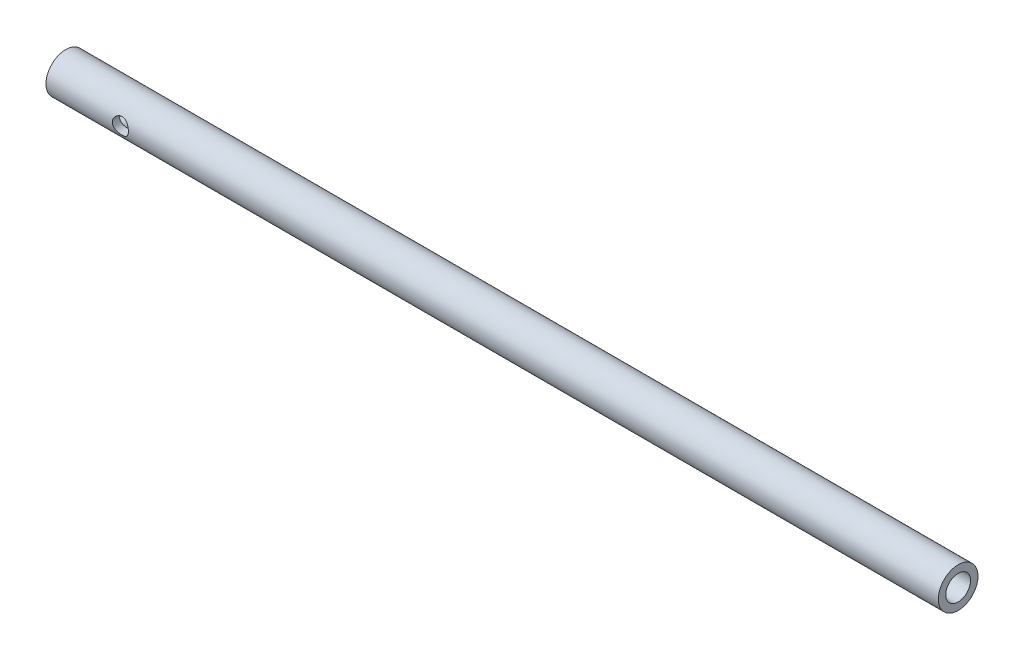
SolidWorks part; units mm, degrees
ref_plane "Front Plane" through (0, 0, 0) normal (0, 0, 1) x (1, 0, 0)
ref_plane "Top Plane" through (0, 0, 0) normal (0, 1, 0) x (1, 0, 0)
ref_plane "Right Plane" through (0, 0, 0) normal (1, 0, 0) x (0, 0, -1)
sketch "Sketch1" plane through (0, 0, 0) normal (1, 0, 0) x (0, 0, -1)
  circle A0 centre (0, 0) radius 16
  circle A1 centre (0, 0) radius 10
  dimension "D1" = 32
  dimension "D2" = 20
extrude "Boss-Extrude1" add sketch "Sketch1" against normal blind 720
sketch "Sketch2" plane through (0, 0, 0) normal (0, 0, 1) x (1, 0, 0)
  line L0 (-720, 16) -> (-720, -16) construction
  line L1 (-720, 0) -> (-604.8317, 0) construction
  circle A0 centre (-660, 0) radius 6.5
  dimension "D1" = 13
  dimension "D2" = 60
extrude "Cut-Extrude1" cut sketch "Sketch2" against normal mid plane 59
